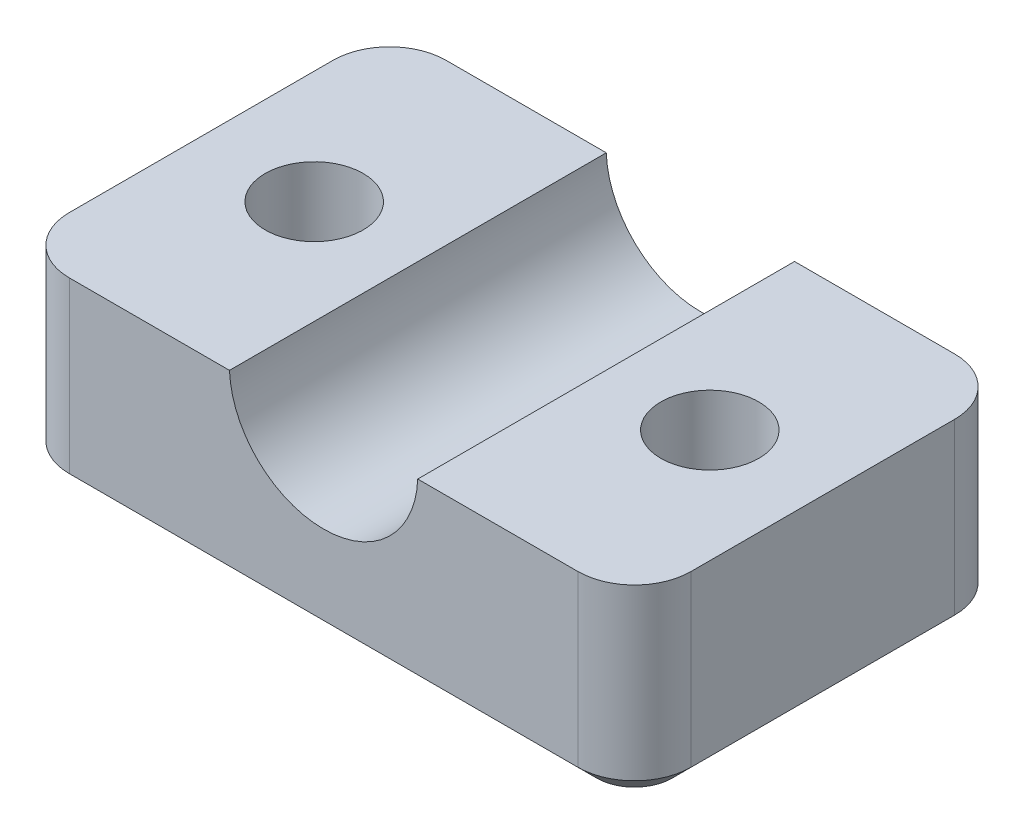
SolidWorks part; units mm, degrees
material "ABS"
ref_plane "Front Plane" through (0, 0, 0) normal (0, 0, 1) x (1, 0, 0)
ref_plane "Top Plane" through (0, 0, 0) normal (0, 1, 0) x (1, 0, 0)
ref_plane "Right Plane" through (0, 0, 0) normal (1, 0, 0) x (0, 0, -1)
sketch "Sketch1" plane through (0, 0, 0) normal (0, 1, 0) x (1, 0, 0)
  line L0 (-50.7915, 0) -> (50.7915, 0) construction
  line L1 (0, -10) -> (0, 10) construction
  line L2 (-13.5, -10) -> (13.5, -10)
  line L3 (-16.5, -7) -> (-16.5, 7)
  line L4 (-13.5, 10) -> (13.5, 10)
  line L5 (16.5, -7) -> (16.5, 7)
  line L6 (-16.5, -10) -> (16.5, 10) construction
  line L7 (-16.5, 10) -> (16.5, -10) construction
  arc A0 (-16.5, -7) -> (-13.5, -10) centre (-13.5, -7) ccw
  arc A1 (13.5, -10) -> (16.5, -7) centre (13.5, -7) ccw
  arc A2 (16.5, 7) -> (13.5, 10) centre (13.5, 7) ccw
  arc A3 (-13.5, 10) -> (-16.5, 7) centre (-13.5, 7) ccw
  circle A4 centre (10.5, 0) radius 2.6
  circle A5 centre (-10.5, 0) radius 2.6
  point P3 (0, 0)
  dimension "D3" = 3
  dimension "D4" = 5.2
  dimension "D5" = 10.5
  dimension "D1" = 33
  dimension "D2" = 20
extrude "Boss-Extrude3" add sketch "Sketch1" along normal blind 10
sketch "Sketch5" plane through (0, 0, -10) normal (0, 0, -1) x (-1, 0, 0)
  line L0 (0, 0) -> (0, 17.6887) construction
  line L1 (-13.5, 0) -> (13.5, 0) construction
  circle A0 centre (0, 10.2) radius 5
  dimension "D1" = 10.2
  dimension "D2" = 10
extrude "Cut-Extrude3" cut sketch "Sketch5" against normal up to surface (20 mm away) up to face at (0, 5, 10)
chamfer "Chamfer1" distance 1 angle 45 8 edges at (-15.6213, 0, -9.1213) (-16.5, 0, 0) (0, 0, -10) (-15.6213, 0, 9.1213) (15.6213, 0, -9.1213) (0, 0, 10) (16.5, 0, 0) (15.6213, 0, 9.1213)
